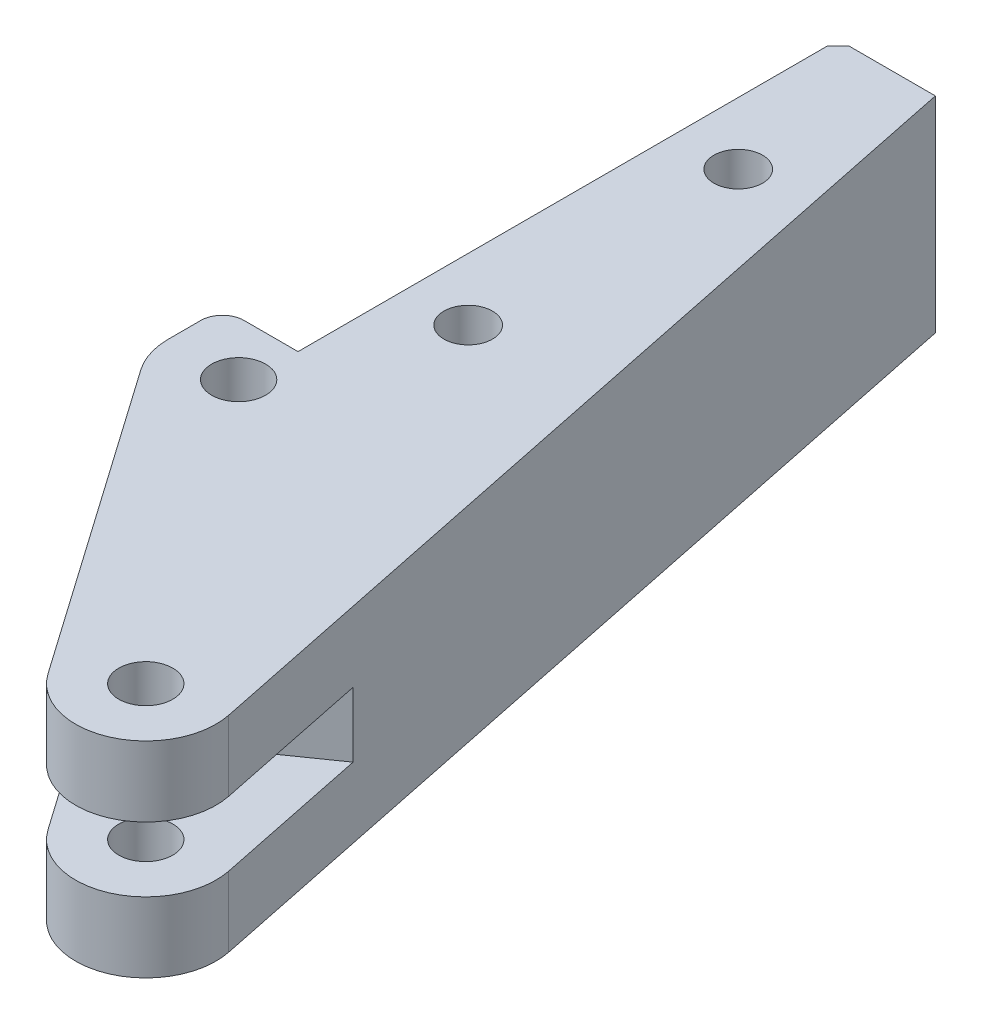
SolidWorks part; units mm, degrees
ref_plane "Plan de face" through (0, 0, 0) normal (0, 0, 1) x (1, 0, 0)
ref_plane "Plan de dessus" through (0, 0, 0) normal (0, 1, 0) x (1, 0, 0)
ref_plane "Plan de droite" through (0, 0, 0) normal (1, 0, 0) x (0, 0, -1)
sketch "Esquisse1" plane through (0, 20, 0) normal (0, 1, 0) x (1, 0, 0)
  line L0 (25.6736, 38.4191) -> (25.6736, -16.5809)
  line L1 (38.6736, 38.4191) -> (38.6736, -12.6397)
  line L2 (46.9242, -48.9795) -> (26.8491, -20.3092)
  line L3 (57.5732, -41.523) -> (39.7586, -16.0812)
  line L6 (38.6736, 38.4191) -> (25.6736, 38.4191)
  arc A0 (38.6736, 38.4191) -> (25.6736, 38.4191) centre (32.1736, 38.4191) ccw construction
  arc A1 (25.6736, -16.5809) -> (26.8491, -20.3092) centre (32.1736, -16.5809) ccw
  arc A2 (46.9242, -48.9795) -> (57.5732, -41.523) centre (52.2487, -45.2513) ccw
  arc A3 (38.6736, -12.6397) -> (39.7586, -16.0812) centre (44.6736, -12.6397) ccw
  circle A4 centre (32.1736, -16.5809) radius 6.5 construction
  dimension "D1" = 6
  dimension "D2" = 13
  dimension "D3" = 55
extrude "Boss.-Extru.2" add sketch "Esquisse1" along normal blind 19
sketch "Esquisse3" plane through (0, 39, 0) normal (0, 1, 0) x (1, 0, 0)
  circle A0 centre (32.1736, -16.5809) radius 2.5
  circle A1 centre (52.2487, -45.2513) radius 2.5
  dimension "D1" = 5
extrude "Enlèv. mat.-Extru.1" cut sketch "Esquisse3" against normal through all
ref_plane "Plan1" through (0, 29.5, 0) normal (0, 1, 0) x (1, 0, 0)
sketch "Esquisse4" plane through (0, 29.5, 0) normal (0, 1, 0) x (1, 0, 0)
  line L0 (57.5732, -41.523) -> (51.2639, -32.5123)
  line L1 (57.5732, -41.523) -> (39.7586, -16.0812) construction
  line L2 (51.2639, -32.5123) -> (40.6149, -39.9688)
  line L3 (26.8491, -20.3092) -> (46.9242, -48.9795) construction
  line L4 (40.6149, -39.9688) -> (46.9242, -48.9795)
  arc A0 (46.9242, -48.9795) -> (57.5732, -41.523) centre (52.2487, -45.2513) ccw
  circle A1 centre (52.2487, -45.2513) radius 2.5 construction
  dimension "D1" = 11
extrude "Enlèv. mat.-Extru.2" cut sketch "Esquisse4" against normal mid plane 6
chamfer "Chanfrein1" distance 4 angle 45 1 edges at (40.6149, 29.5, 39.9688)
sketch "Esquisse5" plane through (38.6736, 0, 0) normal (1, 0, 0) x (0, 0, -1)
  line L0 (38.4191, 29.5) -> (-12.6397, 29.5) construction
  line L2 (-12.6397, 39) -> (-12.6397, 20) construction
  line L4 (38.4191, 39) -> (38.4191, 20) construction
  circle A0 centre (-1.5809, 29.5) radius 2
  circle A1 centre (28.4191, 29.5) radius 2
  dimension "D1" = 30
  dimension "D3" = 4
  dimension "D2" = 10
extrude "Enlèv. mat.-Extru.3" [suppressed] cut sketch "Esquisse5" against normal up to surface (12 mm away)
sketch "Esquisse7" plane through (0, 39, 0) normal (0, 1, 0) x (1, 0, 0)
  line L1 (25.6736, 38.4191) -> (32.6736, 38.4191)
  line L2 (25.6736, 38.4191) -> (25.6736, -11.5809)
  line L3 (25.6736, -11.5809) -> (32.6736, -11.5809)
  line L4 (32.6736, 38.4191) -> (32.6736, -11.5809)
  line L5 (25.6736, 38.4191) -> (25.6736, -16.5809) construction
  dimension "D1" = 7
  dimension "D2" = 50
extrude "Enlèv. mat.-Extru.4" cut sketch "Esquisse7" against normal up to surface (19 mm away) up to face at (52.2487, 20, 47.7513)
sketch "Esquisse8" plane through (0, 39, 0) normal (0, 1, 0) x (1, 0, 0)
  line L0 (38.6736, 38.4191) -> (41.6736, 38.4191)
  line L1 (57.5732, -41.523) -> (39.7586, -16.0812) construction
  line L2 (38.6736, -12.6397) -> (38.6736, 38.4191) construction
  line L3 (57.5732, -41.523) -> (39.7586, -16.0812)
  line L4 (38.6736, -12.6397) -> (38.6736, 38.4191)
  line L5 (58.6154, -43.9416) -> (57.5732, -43.9416)
  line L6 (57.5732, -43.9416) -> (57.5732, -41.523)
  line L7 (41.6736, 38.4191) -> (58.6154, -43.9416)
  arc A0 (46.9242, -48.9795) -> (57.5732, -41.523) centre (52.2487, -45.2513) ccw construction
  arc A1 (38.6736, -12.6397) -> (39.7586, -16.0812) centre (44.6736, -12.6397) ccw construction
  arc A2 (38.6736, -12.6397) -> (39.7586, -16.0812) centre (44.6736, -12.6397) ccw
  dimension "D1" = 3
extrude "Boss.-Extru.3" add sketch "Esquisse8" against normal up to surface (19 mm away) up to face at (52.2487, 20, 47.7513)
sketch "Esquisse11" plane through (0, 32.5, 0) normal (0, -1, 0) x (1, 0, 0)
  line L0 (51.2639, 32.5123) -> (43.8915, 37.6745) construction
  line L1 (38.3206, 36.6922) -> (43.8915, 37.6745) construction
  line L2 (38.3206, 36.6922) -> (46.9242, 48.9795) construction
  line L3 (51.2639, 32.5123) -> (43.8915, 37.6745)
  line L4 (38.3206, 36.6922) -> (43.8915, 37.6745)
  line L5 (38.3206, 36.6922) -> (46.9242, 48.9795)
  line L6 (51.2639, 32.5123) -> (55.6348, 29.4518)
  line L8 (55.6348, 29.4518) -> (58.6154, 43.9416)
  arc A0 (58.6154, 43.9416) -> (46.9242, 48.9795) centre (52.2487, 45.2513) ccw construction
  arc A1 (58.6154, 43.9416) -> (46.9242, 48.9795) centre (52.2487, 45.2513) ccw
extrude "Enlèv. mat.-Extru.7" cut sketch "Esquisse11" along normal up to surface (6 mm away) up to face at (50.8876, 26.5, 41.4321)
ref_plane "symetrie_nervure" through (0, 29.5, 0) normal (0, 1, 0) x (1, 0, 0)
mirror "Symétrie1" [suppressed] about plane through (0, 29.5, 0) normal (0, 1, 0)
fillet "Congé2" radius 2 1 edges at (25.6736, 29.5, 11.5809)
chamfer "Chanfrein2" distance 1 angle 45 1 edges at (32.6736, 29.5, -38.4191)
fillet "Congé3" [suppressed] radius 2.4
sketch "Esquisse9" plane through (0, 39, 0) normal (0, 1, 0) x (1, 0, 0)
  line L0 (38.4236, 23.4191) -> (38.4236, -1.5809) construction
  line L1 (32.6736, -11.5809) -> (32.6736, 37.4191) construction
  line L2 (27.6736, -11.5809) -> (32.6736, -11.5809) construction
  circle A0 centre (38.4236, 23.4191) radius 2.25
  circle A1 centre (38.4236, -1.5809) radius 2.25
  dimension "D2" = 4.5
  dimension "D1" = 3.5
  dimension "D3" = 25
  dimension "D4" = 10
extrude "Enlèv. mat.-Extru.5" cut sketch "Esquisse9" against normal through all
